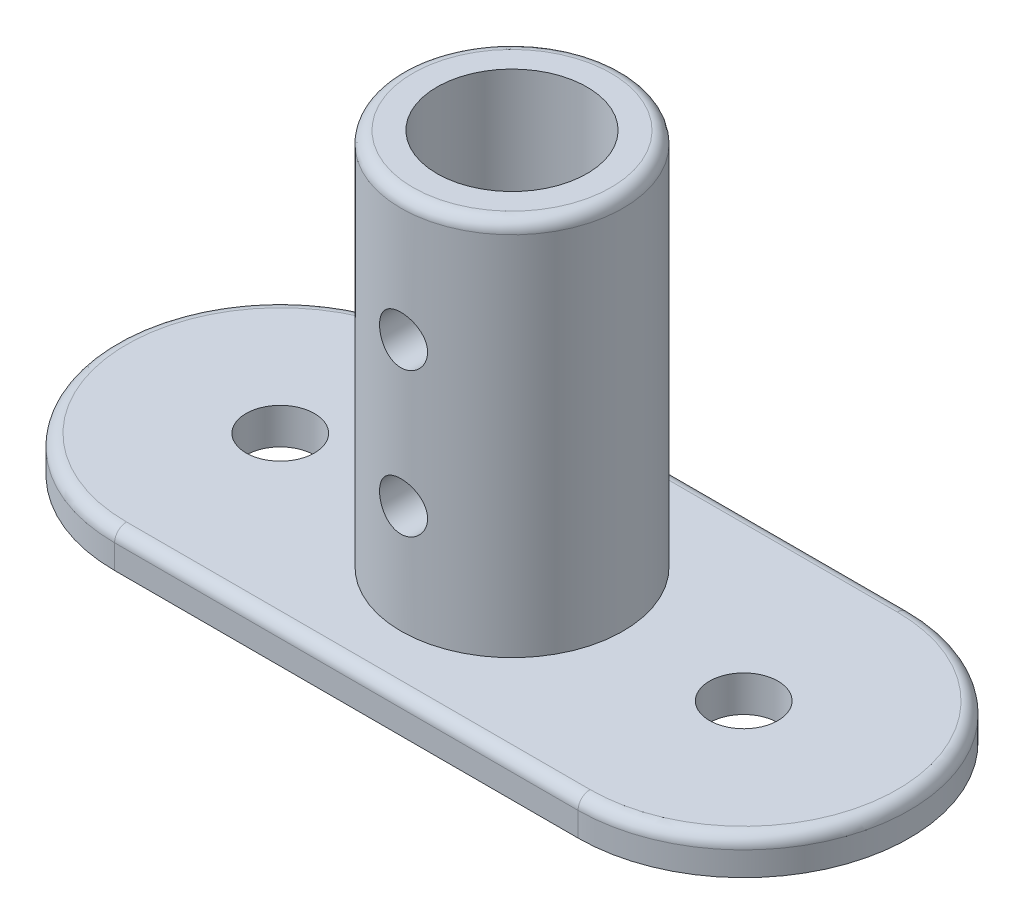
SolidWorks part; units mm, degrees
ref_plane "Front Plane" through (0, 0, 0) normal (0, 0, 1) x (1, 0, 0)
ref_plane "Top Plane" through (0, 0, 0) normal (0, 1, 0) x (1, 0, 0)
ref_plane "Right Plane" through (0, 0, 0) normal (1, 0, 0) x (0, 0, -1)
sketch "Sketch1" plane through (0, 0, 0) normal (0, 1, 0) x (1, 0, 0)
  line L0 (-49.022, 0) -> (49.022, 0) construction
  line L1 (-49.022, 35.052) -> (49.022, 35.052)
  line L2 (-49.022, -35.052) -> (49.022, -35.052)
  arc A0 (-49.022, 35.052) -> (-49.022, -35.052) centre (-49.022, 0) ccw
  arc A1 (49.022, -35.052) -> (49.022, 35.052) centre (49.022, 0) ccw
  circle A2 centre (-49.022, 0) radius 7.239
  circle A3 centre (49.022, 0) radius 7.239
  circle A4 centre (0, 0) radius 7.239
  point P3 (0, 0)
  dimension "D3" = 14.478
  dimension "D1" = 98.044
  dimension "D2" = 70.104
extrude "Boss-Extrude1" add sketch "Sketch1" along normal blind 7.62
sketch "Sketch2" plane through (0, 7.62, 0) normal (0, 1, 0) x (1, 0, 0)
  circle A0 centre (0, 0) radius 15.875
  circle A1 centre (0, 0) radius 23.495
  dimension "D1" = 31.75
  dimension "D2" = 7.62
extrude "Boss-Extrude2" add sketch "Sketch2" along normal blind 80.01
fillet "Fillet1" radius 2.54 5 edges at (-84.074, 7.62, 0) (0, 7.62, -35.052) (84.074, 7.62, 0) (0, 87.63, 23.495) (0, 7.62, 35.052)
sketch "Sketch4" plane through (0, 0, 0) normal (0, 0, 1) x (1, 0, 0)
  circle A0 centre (0, 60.96) radius 5.08
  circle A1 centre (0, 30.48) radius 5.08
  point P4 (0, 0)
  point P6 (0, 0)
  point P7 (0, 0)
  dimension "D3" = 10.16
  dimension "D1" = 30.48
  dimension "D2" = 30.48
extrude "Cut-Extrude1" cut sketch "Sketch4" along normal blind 80.01
